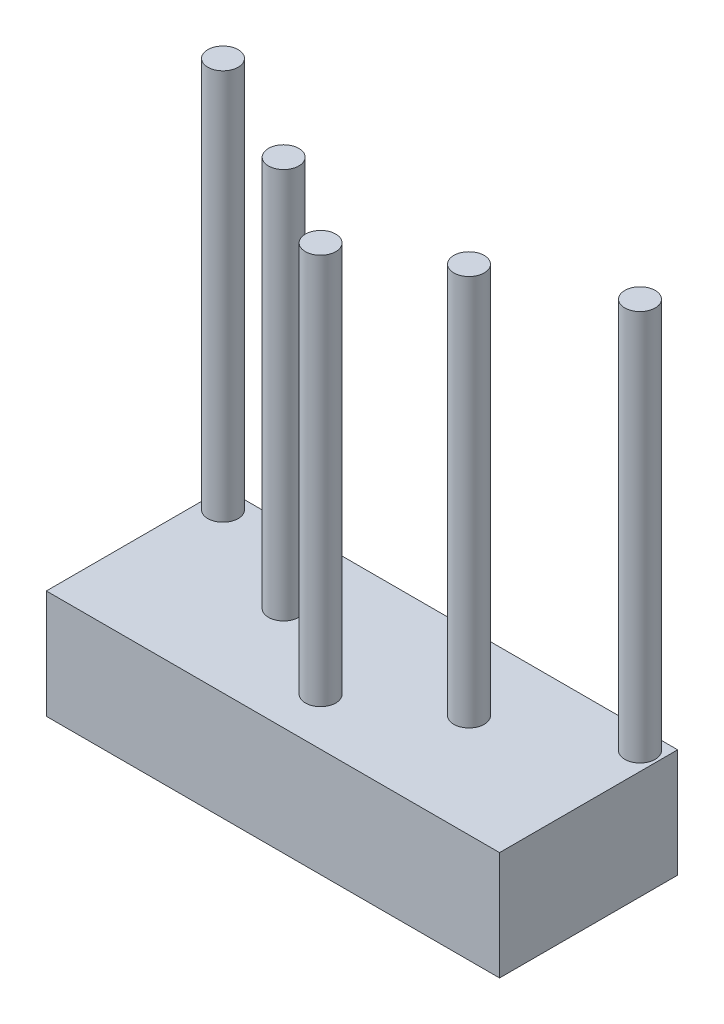
SolidWorks part; units mm, degrees
ref_plane "Front Plane" through (0, 0, 0) normal (0, 0, 1) x (1, 0, 0)
ref_plane "Top Plane" through (0, 0, 0) normal (0, 1, 0) x (1, 0, 0)
ref_plane "Right Plane" through (0, 0, 0) normal (1, 0, 0) x (0, 0, -1)
sketch "Sketch1" plane through (0, 0, 0) normal (0, 1, 0) x (1, 0, 0)
  line L1 (-39.751, 15.621) -> (39.751, 15.621)
  line L2 (-39.751, 15.621) -> (-39.751, -15.621)
  line L3 (-39.751, -15.621) -> (39.751, -15.621)
  line L4 (39.751, 15.621) -> (39.751, -15.621)
  dimension "D1" = 31.242
  dimension "D2" = 79.502
  dimension "D3" = 39.751
  dimension "D4" = 15.621
extrude "Boss-Extrude1" add sketch "Sketch1" along normal blind 19.05
sketch "Sketch2" plane through (0, 19.05, 0) normal (0, 1, 0) x (1, 0, 0)
  line L0 (-36.576, 12.192) -> (-39.243, 12.192) construction
  line L1 (-16.256, 2.5151) -> (-18.923, 2.5151) construction
  line L2 (0, -7.2639) -> (-2.667, -7.2639) construction
  line L3 (16.256, 2.5151) -> (13.589, 2.5151) construction
  line L4 (36.576, 12.192) -> (33.909, 12.192) construction
  line L5 (-36.576, 12.192) -> (-33.909, 12.192) construction
  line L6 (-16.256, 2.5151) -> (-13.589, 2.5151) construction
  line L7 (16.256, 2.5151) -> (18.923, 2.5151) construction
  line L8 (0, -7.2639) -> (2.667, -7.2639) construction
  line L9 (36.576, 12.192) -> (39.243, 12.192) construction
  circle A0 centre (-36.576, 12.192) radius 2.667
  circle A4 centre (-16.256, 2.5151) radius 2.667
  circle A5 centre (0, -7.2639) radius 2.667
  circle A6 centre (16.256, 2.5151) radius 2.667
  circle A7 centre (36.576, 12.192) radius 2.667
  point P2 (0, 0)
  point P22 (0, 0)
  point P23 (0, 0)
  point P24 (0, 0)
  point P25 (0, 0)
  point P26 (0, 0)
  point P27 (0, 0)
  point P28 (-133.5263, 41.5631)
  dimension "D5" = 0
  dimension "D10" = 16.256
  dimension "D11" = 36.576
  dimension "D12" = 36.576
  dimension "D4" = 5.334
  dimension "D2" = 0
  dimension "D3" = 12.192
  dimension "D6" = 19.4559
  dimension "D7" = 9.779
  dimension "D8" = 0
  dimension "D9" = 16.256
extrude "Boss-Extrude2" add sketch "Sketch2" along normal blind 68.58
equation "\"0..8in\"=0.625491"
